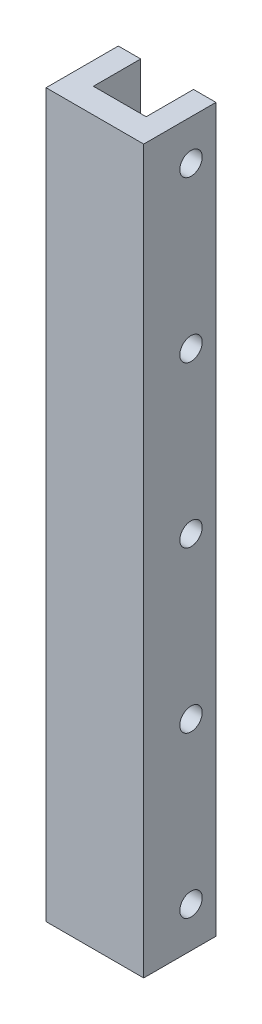
SolidWorks part; units mm, degrees
ref_plane "Спереди" through (0, 0, 0) normal (0, 0, 1) x (1, 0, 0)
ref_plane "Сверху" through (0, 0, 0) normal (0, 1, 0) x (1, 0, 0)
ref_plane "Справа" through (0, 0, 0) normal (1, 0, 0) x (0, 0, -1)
sketch "Эскиз1" plane through (0, 0, 0) normal (0, 1, 0) x (1, 0, 0)
  line L0 (0, 0) -> (10.6, 0)
  line L1 (10.6, 0) -> (10.6, 9.5)
  line L2 (10.6, 9.5) -> (15.1, 9.5)
  line L3 (15.1, 9.5) -> (15.1, -5)
  line L4 (15.1, -5) -> (-4.5, -5)
  line L5 (-4.5, -5) -> (-4.5, 9.5)
  line L6 (-4.5, 9.5) -> (0, 9.5)
  line L7 (0, 9.5) -> (0, 0)
  dimension "D1" = 9.5
  dimension "D2" = 4.5
  dimension "D3" = 4.5
  dimension "D4" = 5
  dimension "D5" = 10.6
extrude "Бобышка-Вытянуть1" add sketch "Эскиз1" along normal blind 145
sketch "Эскиз2" plane through (15.1, 0, 0) normal (1, 0, 0) x (0, 0, -1)
  line L0 (9.5, 0) -> (4.5, 0) construction
  line L1 (-5, 0) -> (9.5, 0) construction
  line L2 (4.5, 0) -> (4.5, 8.1) construction
  line L3 (4.5, 8.1) -> (4.5, 40.3) construction
  line L4 (4.5, 40.3) -> (4.5, 72.5) construction
  line L5 (4.5, 72.5) -> (4.5, 104.7) construction
  line L6 (4.5, 104.7) -> (4.5, 136.9) construction
  line L7 (4.5, 136.9) -> (4.5, 145) construction
  line L8 (-5, 145) -> (9.5, 145) construction
  circle A0 centre (4.5, 40.3) radius 2.25
  circle A1 centre (4.5, 8.1) radius 2.25
  circle A2 centre (4.5, 72.5) radius 2.25
  circle A3 centre (4.5, 104.7) radius 2.25
  circle A4 centre (4.5, 136.9) radius 2.25
  dimension "D4" = 4.5
  dimension "D1" = 5
  dimension "D3" = 32.2
  dimension "D5" = 4
extrude "Вырез-Вытянуть1" cut sketch "Эскиз2" against normal through all
